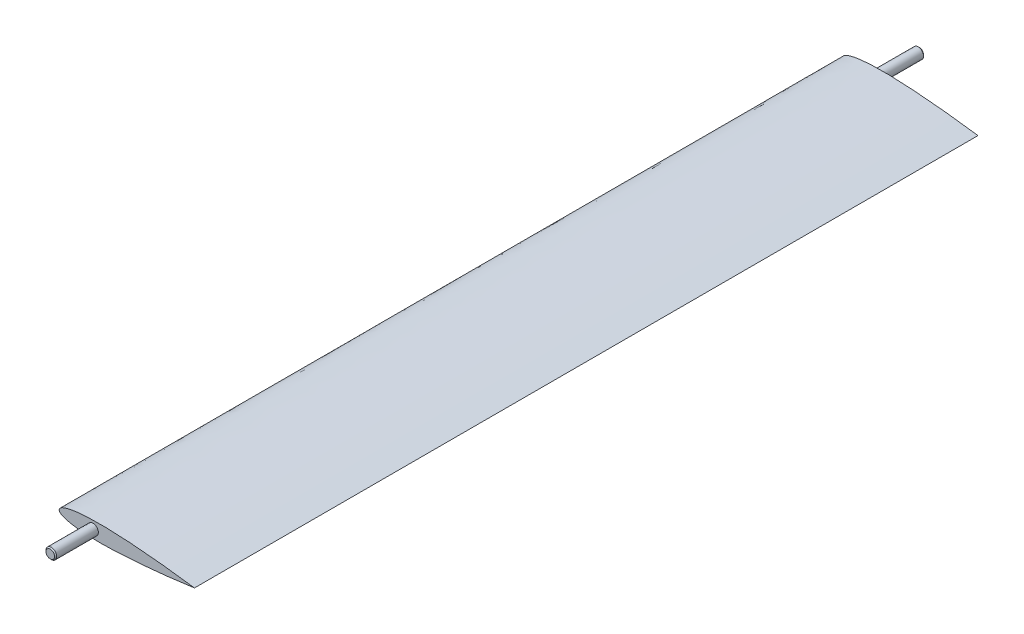
SolidWorks part; units mm, degrees
ref_plane "Front Plane" through (0, 0, 0) normal (0, 0, 1) x (1, 0, 0)
ref_plane "Top Plane" through (0, 0, 0) normal (0, 1, 0) x (1, 0, 0)
ref_plane "Right Plane" through (0, 0, 0) normal (1, 0, 0) x (0, 0, -1)
sketch "Sketch1" plane through (0, 0, 0) normal (0, 0, 1) x (1, 0, 0)
  spline S0 degree 4 poles (0, 0) (0, 0.0338) (0.004, 0.0876) (0.0188, 0.1619) (0.0529, 0.2538) (0.0948, 0.3353) (0.1534, 0.4227) (0.2369, 0.5211) (0.3605, 0.6372) (0.5499, 0.7786) (0.8526, 0.956) (1.3384, 1.1736) (2.127, 1.4362) (3.4448, 1.7454) (5.3549, 2.0271) (7.7765, 2.2199) (10.5668, 2.2987) (13.4676, 2.2726) (16.3652, 2.1673) (19.2618, 2.0014) (21.7904, 1.8152) (23.961, 1.6308) (25.7603, 1.4638) (27.213, 1.32) (28.9963, 1.135) (30.8336, 0.9292) (32.5761, 0.7242) (34.456, 0.4855) (35.7546, 0.3158) (37.5832, 0.0606) (38.6246, -0.0918) (40.1506, -0.3234) (40.8918, -0.4449) (41.4992, -0.5419) (41.6482, -0.5684) (41.8081, -0.5941) knots 0 0 0 0 0 0.003164 0.005066 0.007068 0.009183 0.011752 0.014927 0.019157 0.02508 0.033903 0.047807 0.06905 0.103021 0.160853 0.228932 0.29701 0.365089 0.433167 0.501246 0.569325 0.603364 0.637403 0.671442 0.705482 0.77356 0.8076 0.841639 0.875678 0.909717 0.954859 0.977429 0.988715 1 1 1 1 1 construction
  spline S1 degree 4 poles (0, 0) (0, 0.0338) (0.004, 0.0876) (0.0188, 0.1619) (0.0529, 0.2538) (0.0948, 0.3353) (0.1534, 0.4227) (0.2369, 0.5211) (0.3605, 0.6372) (0.5499, 0.7786) (0.8526, 0.956) (1.3384, 1.1736) (2.127, 1.4362) (3.4448, 1.7454) (5.3549, 2.0271) (7.7765, 2.2199) (10.5668, 2.2987) (13.4676, 2.2726) (16.3652, 2.1673) (19.2618, 2.0014) (21.7904, 1.8152) (23.961, 1.6308) (25.7603, 1.4638) (27.213, 1.32) (28.9963, 1.135) (30.8336, 0.9292) (32.5761, 0.7242) (34.456, 0.4855) (35.7518, 0.3161) (37.0155, 0.1398) (37.6653, 0.047) (37.9889, 0) knots 0 0 0 0 0 0.003164 0.005066 0.007068 0.009183 0.011752 0.014927 0.019157 0.02508 0.033903 0.047807 0.06905 0.103021 0.160853 0.228932 0.29701 0.365089 0.433167 0.501246 0.569325 0.603364 0.637403 0.671442 0.705482 0.77356 0.8076 0.841639 0.875678 0.909427 0.909427 0.909427 0.909427 0.909427
  spline S2 degree 4 poles (0, 0) (0, -0.0338) (0.004, -0.0876) (0.0188, -0.1619) (0.0529, -0.2538) (0.0948, -0.3353) (0.1534, -0.4227) (0.2369, -0.5211) (0.3605, -0.6372) (0.5499, -0.7786) (0.8526, -0.956) (1.3384, -1.1736) (2.127, -1.4362) (3.4448, -1.7454) (5.3549, -2.0271) (7.7765, -2.2199) (10.5668, -2.2987) (13.4676, -2.2726) (16.3652, -2.1673) (19.2618, -2.0014) (21.7904, -1.8152) (23.961, -1.6308) (25.7603, -1.4638) (27.213, -1.32) (28.9963, -1.135) (30.8336, -0.9292) (32.5761, -0.7242) (34.456, -0.4855) (35.7546, -0.3158) (37.5832, -0.0606) (38.6246, 0.0918) (40.1506, 0.3234) (40.8918, 0.4449) (41.4992, 0.5419) (41.6482, 0.5684) (41.8081, 0.5941) knots 0 0 0 0 0 0.003164 0.005066 0.007068 0.009183 0.011752 0.014927 0.019157 0.02508 0.033903 0.047807 0.06905 0.103021 0.160853 0.228932 0.29701 0.365089 0.433167 0.501246 0.569325 0.603364 0.637403 0.671442 0.705482 0.77356 0.8076 0.841639 0.875678 0.909717 0.954859 0.977429 0.988715 1 1 1 1 1 construction
  spline S3 degree 4 poles (0, 0) (0, -0.0338) (0.004, -0.0876) (0.0188, -0.1619) (0.0529, -0.2538) (0.0948, -0.3353) (0.1534, -0.4227) (0.2369, -0.5211) (0.3605, -0.6372) (0.5499, -0.7786) (0.8526, -0.956) (1.3384, -1.1736) (2.127, -1.4362) (3.4448, -1.7454) (5.3549, -2.0271) (7.7765, -2.2199) (10.5668, -2.2987) (13.4676, -2.2726) (16.3652, -2.1673) (19.2618, -2.0014) (21.7904, -1.8152) (23.961, -1.6308) (25.7603, -1.4638) (27.213, -1.32) (28.9963, -1.135) (30.8336, -0.9292) (32.5761, -0.7242) (34.456, -0.4855) (35.7518, -0.3161) (37.0155, -0.1398) (37.6653, -0.047) (37.9889, 0) knots 0 0 0 0 0 0.003164 0.005066 0.007068 0.009183 0.011752 0.014927 0.019157 0.02508 0.033903 0.047807 0.06905 0.103021 0.160853 0.228932 0.29701 0.365089 0.433167 0.501246 0.569325 0.603364 0.637403 0.671442 0.705482 0.77356 0.8076 0.841639 0.875678 0.909427 0.909427 0.909427 0.909427 0.909427
extrude "Boss-Extrude1" add sketch "Sketch1" along normal blind 220
sketch "Sketch6" plane through (0, 0, 0) normal (0, 0, 1) x (1, 0, 0)
  spline S0 degree 4 poles (0, -0.25) (0, -0.2135) (0.0045, -0.1583) (0.0202, -0.0829) (0.0559, 0.0105) (0.0983, 0.0912) (0.1583, 0.1792) (0.2445, 0.279) (0.3727, 0.3974) (0.5692, 0.5414) (0.8849, 0.7226) (1.3947, 0.9456) (2.2248, 1.214) (3.6278, 1.5305) (5.6548, 1.8111) (8.218, 1.9934) (11.1671, 2.0532) (14.2174, 2.0036) (17.2636, 1.8729) (20.309, 1.6801) (22.9666, 1.4698) (25.2488, 1.2635) (27.1389, 1.0782) (28.6686, 0.9183) (30.1605, 0.7557) (31.7144, 0.5748) (33.5365, 0.3564) (35.5523, 0.0925) (37.2418, -0.137) (39.553, -0.4811) (40.6664, -0.6559) (42.2569, -0.9161) (43.0499, -1.057) (43.6793, -1.1661) (43.843, -1.1976) (44.0078, -1.2265) knots 0 0 0 0 0 0.00324 0.004942 0.006838 0.008891 0.01136 0.014425 0.018582 0.024427 0.033056 0.046837 0.068147 0.10216 0.161218 0.229245 0.297273 0.3653 0.433328 0.501355 0.569383 0.603397 0.63741 0.671424 0.705438 0.739452 0.773465 0.841493 0.875507 0.90952 0.95476 0.97738 0.98869 1 1 1 1 1 construction
  spline S1 degree 4 poles (0.0535, 0) (0.0676, 0.0323) (0.0966, 0.0884) (0.1503, 0.1699) (0.2445, 0.279) (0.3727, 0.3974) (0.5692, 0.5414) (0.8849, 0.7226) (1.3947, 0.9456) (2.2248, 1.214) (3.6278, 1.5305) (5.6548, 1.8111) (8.218, 1.9934) (11.1671, 2.0532) (14.2174, 2.0036) (17.2636, 1.8729) (20.309, 1.6801) (22.9666, 1.4698) (25.2488, 1.2635) (27.1389, 1.0782) (28.6686, 0.9183) (30.1605, 0.7557) (31.7144, 0.5748) (33.3534, 0.3783) (34.7466, 0.1977) (35.6668, 0.0753) (36.2182, 0) knots 0.005744 0.005744 0.005744 0.005744 0.005744 0.008891 0.01136 0.014425 0.018582 0.024427 0.033056 0.046837 0.068147 0.10216 0.161218 0.229245 0.297273 0.3653 0.433328 0.501355 0.569383 0.603397 0.63741 0.671424 0.705438 0.739452 0.773465 0.824409 0.824409 0.824409 0.824409 0.824409
  spline S2 degree 4 poles (0.0535, 0) (0.0676, -0.0323) (0.0966, -0.0884) (0.1503, -0.1699) (0.2445, -0.279) (0.3727, -0.3974) (0.5692, -0.5414) (0.8849, -0.7226) (1.3947, -0.9456) (2.2248, -1.214) (3.6278, -1.5305) (5.6548, -1.8111) (8.218, -1.9934) (11.1671, -2.0532) (14.2174, -2.0036) (17.2636, -1.8729) (20.309, -1.6801) (22.9666, -1.4698) (25.2488, -1.2635) (27.1389, -1.0782) (28.6686, -0.9183) (30.1605, -0.7557) (31.7144, -0.5748) (33.3534, -0.3783) (34.7466, -0.1977) (35.6668, -0.0753) (36.2182, 0) knots 0.005744 0.005744 0.005744 0.005744 0.005744 0.008891 0.01136 0.014425 0.018582 0.024427 0.033056 0.046837 0.068147 0.10216 0.161218 0.229245 0.297273 0.3653 0.433328 0.501355 0.569383 0.603397 0.63741 0.671424 0.705438 0.739452 0.773465 0.824409 0.824409 0.824409 0.824409 0.824409
extrude "Cut-Extrude4" cut sketch "Sketch6" along normal through all
sketch "Sketch8" plane through (0, 0, 0) normal (0, 0, 1) x (1, 0, 0)
  spline S0 degree 4 poles (0, 0) (0, 0.0338) (0.004, 0.0876) (0.0188, 0.1619) (0.0529, 0.2538) (0.0948, 0.3353) (0.1534, 0.4227) (0.2369, 0.5211) (0.3605, 0.6372) (0.5499, 0.7786) (0.8526, 0.956) (1.3384, 1.1736) (2.127, 1.4362) (3.4448, 1.7454) (5.3549, 2.0271) (7.7765, 2.2199) (10.5668, 2.2987) (13.4676, 2.2726) (16.3652, 2.1673) (19.2618, 2.0014) (21.7904, 1.8152) (23.961, 1.6308) (25.7603, 1.4638) (27.213, 1.32) (28.9963, 1.135) (30.8336, 0.9292) (32.5761, 0.7242) (34.456, 0.4855) (35.7546, 0.3158) (37.5832, 0.0606) (38.6246, -0.0918) (40.1506, -0.3234) (40.8918, -0.4449) (41.4992, -0.5419) (41.6482, -0.5684) (41.8081, -0.5941) knots 0 0 0 0 0 0.003164 0.005066 0.007068 0.009183 0.011752 0.014927 0.019157 0.02508 0.033903 0.047807 0.06905 0.103021 0.160853 0.228932 0.29701 0.365089 0.433167 0.501246 0.569325 0.603364 0.637403 0.671442 0.705482 0.77356 0.8076 0.841639 0.875678 0.909717 0.954859 0.977429 0.988715 1 1 1 1 1 construction
  spline S1 degree 4 poles (0, 0) (0, 0.0338) (0.004, 0.0876) (0.0188, 0.1619) (0.0529, 0.2538) (0.0948, 0.3353) (0.1534, 0.4227) (0.2369, 0.5211) (0.3605, 0.6372) (0.5499, 0.7786) (0.8526, 0.956) (1.3384, 1.1736) (2.127, 1.4362) (3.4448, 1.7454) (5.3549, 2.0271) (7.7765, 2.2199) (10.5668, 2.2987) (13.4676, 2.2726) (16.3652, 2.1673) (19.2618, 2.0014) (21.7904, 1.8152) (23.961, 1.6308) (25.7603, 1.4638) (27.213, 1.32) (28.9963, 1.135) (30.8336, 0.9292) (32.5761, 0.7242) (34.456, 0.4855) (35.7518, 0.3161) (37.0155, 0.1398) (37.6653, 0.047) (37.9889, 0) knots 0 0 0 0 0 0.003164 0.005066 0.007068 0.009183 0.011752 0.014927 0.019157 0.02508 0.033903 0.047807 0.06905 0.103021 0.160853 0.228932 0.29701 0.365089 0.433167 0.501246 0.569325 0.603364 0.637403 0.671442 0.705482 0.77356 0.8076 0.841639 0.875678 0.909427 0.909427 0.909427 0.909427 0.909427
  spline S2 degree 4 poles (0, 0) (0, -0.0338) (0.004, -0.0876) (0.0188, -0.1619) (0.0529, -0.2538) (0.0948, -0.3353) (0.1534, -0.4227) (0.2369, -0.5211) (0.3605, -0.6372) (0.5499, -0.7786) (0.8526, -0.956) (1.3384, -1.1736) (2.127, -1.4362) (3.4448, -1.7454) (5.3549, -2.0271) (7.7765, -2.2199) (10.5668, -2.2987) (13.4676, -2.2726) (16.3652, -2.1673) (19.2618, -2.0014) (21.7904, -1.8152) (23.961, -1.6308) (25.7603, -1.4638) (27.213, -1.32) (28.9963, -1.135) (30.8336, -0.9292) (32.5761, -0.7242) (34.456, -0.4855) (35.7546, -0.3158) (37.5832, -0.0606) (38.6246, 0.0918) (40.1506, 0.3234) (40.8918, 0.4449) (41.4992, 0.5419) (41.6482, 0.5684) (41.8081, 0.5941) knots 0 0 0 0 0 0.003164 0.005066 0.007068 0.009183 0.011752 0.014927 0.019157 0.02508 0.033903 0.047807 0.06905 0.103021 0.160853 0.228932 0.29701 0.365089 0.433167 0.501246 0.569325 0.603364 0.637403 0.671442 0.705482 0.77356 0.8076 0.841639 0.875678 0.909717 0.954859 0.977429 0.988715 1 1 1 1 1 construction
  spline S3 degree 4 poles (0, 0) (0, -0.0338) (0.004, -0.0876) (0.0188, -0.1619) (0.0529, -0.2538) (0.0948, -0.3353) (0.1534, -0.4227) (0.2369, -0.5211) (0.3605, -0.6372) (0.5499, -0.7786) (0.8526, -0.956) (1.3384, -1.1736) (2.127, -1.4362) (3.4448, -1.7454) (5.3549, -2.0271) (7.7765, -2.2199) (10.5668, -2.2987) (13.4676, -2.2726) (16.3652, -2.1673) (19.2618, -2.0014) (21.7904, -1.8152) (23.961, -1.6308) (25.7603, -1.4638) (27.213, -1.32) (28.9963, -1.135) (30.8336, -0.9292) (32.5761, -0.7242) (34.456, -0.4855) (35.7518, -0.3161) (37.0155, -0.1398) (37.6653, -0.047) (37.9889, 0) knots 0 0 0 0 0 0.003164 0.005066 0.007068 0.009183 0.011752 0.014927 0.019157 0.02508 0.033903 0.047807 0.06905 0.103021 0.160853 0.228932 0.29701 0.365089 0.433167 0.501246 0.569325 0.603364 0.637403 0.671442 0.705482 0.77356 0.8076 0.841639 0.875678 0.909427 0.909427 0.909427 0.909427 0.909427
extrude "Boss-Extrude2" add sketch "Sketch8" along normal blind 3
sketch "Sketch9" plane through (0, 0, 0) normal (0, 0, 1) x (1, 0, 0)
  spline S0 degree 4 poles (0, 0) (0, 0.0338) (0.004, 0.0876) (0.0188, 0.1619) (0.0529, 0.2538) (0.0948, 0.3353) (0.1534, 0.4227) (0.2369, 0.5211) (0.3605, 0.6372) (0.5499, 0.7786) (0.8526, 0.956) (1.3384, 1.1736) (2.127, 1.4362) (3.4448, 1.7454) (5.3549, 2.0271) (7.7765, 2.2199) (10.5668, 2.2987) (13.4676, 2.2726) (16.3652, 2.1673) (19.2618, 2.0014) (21.7904, 1.8152) (23.961, 1.6308) (25.7603, 1.4638) (27.213, 1.32) (28.9963, 1.135) (30.8336, 0.9292) (32.5761, 0.7242) (34.456, 0.4855) (35.7546, 0.3158) (37.5832, 0.0606) (38.6246, -0.0918) (40.1506, -0.3234) (40.8918, -0.4449) (41.4992, -0.5419) (41.6482, -0.5684) (41.8081, -0.5941) knots 0 0 0 0 0 0.003164 0.005066 0.007068 0.009183 0.011752 0.014927 0.019157 0.02508 0.033903 0.047807 0.06905 0.103021 0.160853 0.228932 0.29701 0.365089 0.433167 0.501246 0.569325 0.603364 0.637403 0.671442 0.705482 0.77356 0.8076 0.841639 0.875678 0.909717 0.954859 0.977429 0.988715 1 1 1 1 1 construction
  spline S1 degree 4 poles (0, 0) (0, 0.0338) (0.004, 0.0876) (0.0188, 0.1619) (0.0529, 0.2538) (0.0948, 0.3353) (0.1534, 0.4227) (0.2369, 0.5211) (0.3605, 0.6372) (0.5499, 0.7786) (0.8526, 0.956) (1.3384, 1.1736) (2.127, 1.4362) (3.4448, 1.7454) (5.3549, 2.0271) (7.7765, 2.2199) (10.5668, 2.2987) (13.4676, 2.2726) (16.3652, 2.1673) (19.2618, 2.0014) (21.7904, 1.8152) (23.961, 1.6308) (25.7603, 1.4638) (27.213, 1.32) (28.9963, 1.135) (30.8336, 0.9292) (32.5761, 0.7242) (34.456, 0.4855) (35.7518, 0.3161) (37.0155, 0.1398) (37.6653, 0.047) (37.9889, 0) knots 0 0 0 0 0 0.003164 0.005066 0.007068 0.009183 0.011752 0.014927 0.019157 0.02508 0.033903 0.047807 0.06905 0.103021 0.160853 0.228932 0.29701 0.365089 0.433167 0.501246 0.569325 0.603364 0.637403 0.671442 0.705482 0.77356 0.8076 0.841639 0.875678 0.909427 0.909427 0.909427 0.909427 0.909427
  spline S2 degree 4 poles (0, 0) (0, -0.0338) (0.004, -0.0876) (0.0188, -0.1619) (0.0529, -0.2538) (0.0948, -0.3353) (0.1534, -0.4227) (0.2369, -0.5211) (0.3605, -0.6372) (0.5499, -0.7786) (0.8526, -0.956) (1.3384, -1.1736) (2.127, -1.4362) (3.4448, -1.7454) (5.3549, -2.0271) (7.7765, -2.2199) (10.5668, -2.2987) (13.4676, -2.2726) (16.3652, -2.1673) (19.2618, -2.0014) (21.7904, -1.8152) (23.961, -1.6308) (25.7603, -1.4638) (27.213, -1.32) (28.9963, -1.135) (30.8336, -0.9292) (32.5761, -0.7242) (34.456, -0.4855) (35.7546, -0.3158) (37.5832, -0.0606) (38.6246, 0.0918) (40.1506, 0.3234) (40.8918, 0.4449) (41.4992, 0.5419) (41.6482, 0.5684) (41.8081, 0.5941) knots 0 0 0 0 0 0.003164 0.005066 0.007068 0.009183 0.011752 0.014927 0.019157 0.02508 0.033903 0.047807 0.06905 0.103021 0.160853 0.228932 0.29701 0.365089 0.433167 0.501246 0.569325 0.603364 0.637403 0.671442 0.705482 0.77356 0.8076 0.841639 0.875678 0.909717 0.954859 0.977429 0.988715 1 1 1 1 1 construction
  spline S3 degree 4 poles (0, 0) (0, -0.0338) (0.004, -0.0876) (0.0188, -0.1619) (0.0529, -0.2538) (0.0948, -0.3353) (0.1534, -0.4227) (0.2369, -0.5211) (0.3605, -0.6372) (0.5499, -0.7786) (0.8526, -0.956) (1.3384, -1.1736) (2.127, -1.4362) (3.4448, -1.7454) (5.3549, -2.0271) (7.7765, -2.2199) (10.5668, -2.2987) (13.4676, -2.2726) (16.3652, -2.1673) (19.2618, -2.0014) (21.7904, -1.8152) (23.961, -1.6308) (25.7603, -1.4638) (27.213, -1.32) (28.9963, -1.135) (30.8336, -0.9292) (32.5761, -0.7242) (34.456, -0.4855) (35.7518, -0.3161) (37.0155, -0.1398) (37.6653, -0.047) (37.9889, 0) knots 0 0 0 0 0 0.003164 0.005066 0.007068 0.009183 0.011752 0.014927 0.019157 0.02508 0.033903 0.047807 0.06905 0.103021 0.160853 0.228932 0.29701 0.365089 0.433167 0.501246 0.569325 0.603364 0.637403 0.671442 0.705482 0.77356 0.8076 0.841639 0.875678 0.909427 0.909427 0.909427 0.909427 0.909427
extrude "Boss-Extrude3" add sketch "Sketch9" against normal blind 3 from surface at 220 starting at face at (18.9944, 0, 220)
sketch "Sketch10" plane through (0, 0, 0) normal (0, 0, 1) x (1, 0, 0)
  circle A0 centre (9.5, 0) radius 2
sketch "Sketch11" plane through (0, 0, 220) normal (0, 0, 1) x (1, 0, 0)
  circle A0 centre (9.5, 0) radius 1.5
extrude "Boss-Extrude4" add sketch "Sketch11" along normal blind 12
chamfer "Chamfer1" distance 0.3 angle 45 1 edges at (11, 0, 232)
sketch "Sketch12" plane through (0, 0, 0) normal (0, 0, -1) x (-1, 0, 0)
  circle A0 centre (-9.5, 0) radius 1.5
extrude "Boss-Extrude5" add sketch "Sketch12" along normal blind 12
chamfer "Chamfer2" distance 0.3 angle 45 1 edges at (8, 0, -12)
sketch "Sketch14" plane through (0, 0, -12) normal (0, 0, -1) x (-1, 0, 0)
  line L1 (-8.5, 1.7499) -> (-6.3456, 1.7499)
  line L2 (-8.5, 1.7499) -> (-8.5, -1.6159)
  line L3 (-8.5, -1.6159) -> (-6.3456, -1.6159)
  line L4 (-6.3456, 1.7499) -> (-6.3456, -1.6159)
  dimension "D1" = 1
extrude "Cut-Extrude5" cut sketch "Sketch14" against normal blind 6
